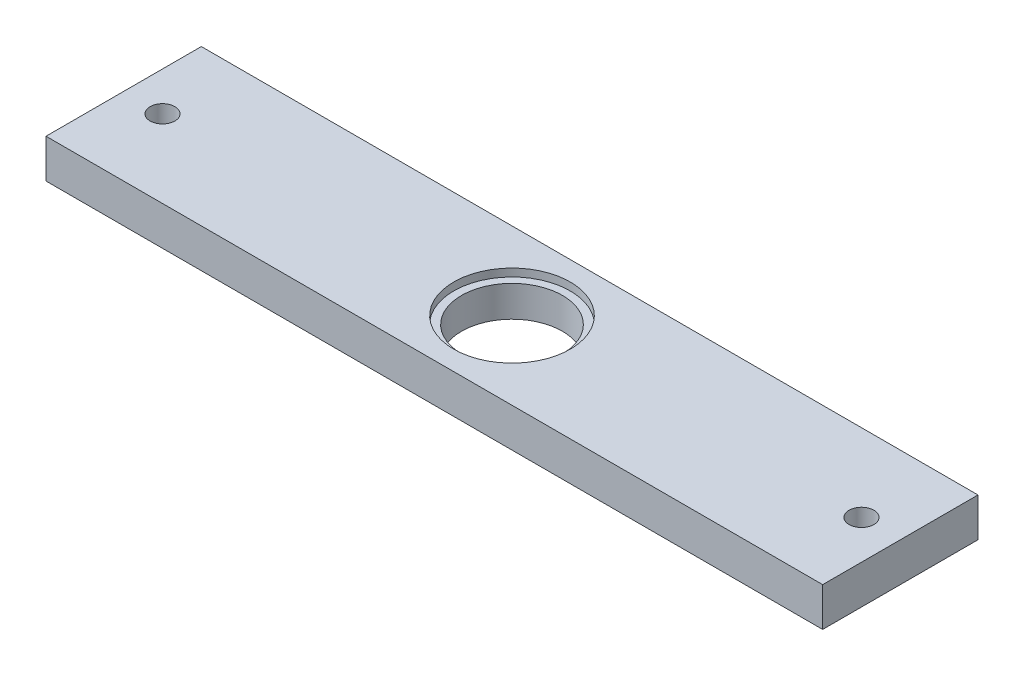
SolidWorks part; units mm, degrees
ref_plane "前视基准面" through (0, 0, 0) normal (0, 0, 1) x (1, 0, 0)
ref_plane "上视基准面" through (0, 0, 0) normal (0, 1, 0) x (1, 0, 0)
ref_plane "右视基准面" through (0, 0, 0) normal (1, 0, 0) x (0, 0, -1)
sketch "草图1" plane through (0, 0, 0) normal (0, 1, 0) x (1, 0, 0)
  line L0 (-45, 0) -> (45, 0) construction
  line L1 (-50, -10) -> (50, -10)
  line L2 (-50, -10) -> (-50, 10)
  line L3 (-50, 10) -> (50, 10)
  line L4 (50, -10) -> (50, 10)
  line L5 (-50, -10) -> (50, 10) construction
  line L6 (-50, 10) -> (50, -10) construction
  circle A0 centre (45, 0) radius 1.6
  circle A1 centre (-45, 0) radius 1.6
  circle A2 centre (0, 0) radius 6.5
  point P0 (0, 0)
  dimension "D3" = 3.2
  dimension "D4" = 13
  dimension "D1" = 20
  dimension "D2" = 100
  dimension "D5" = 90
extrude "凸台-拉伸1" add sketch "草图1" along normal blind 5
sketch "草图2" plane through (0, 5, 0) normal (0, 1, 0) x (1, 0, 0)
  circle A0 centre (0, 0) radius 7.5
  dimension "D1" = 15
extrude "切除-拉伸1" cut sketch "草图2" against normal blind 1
